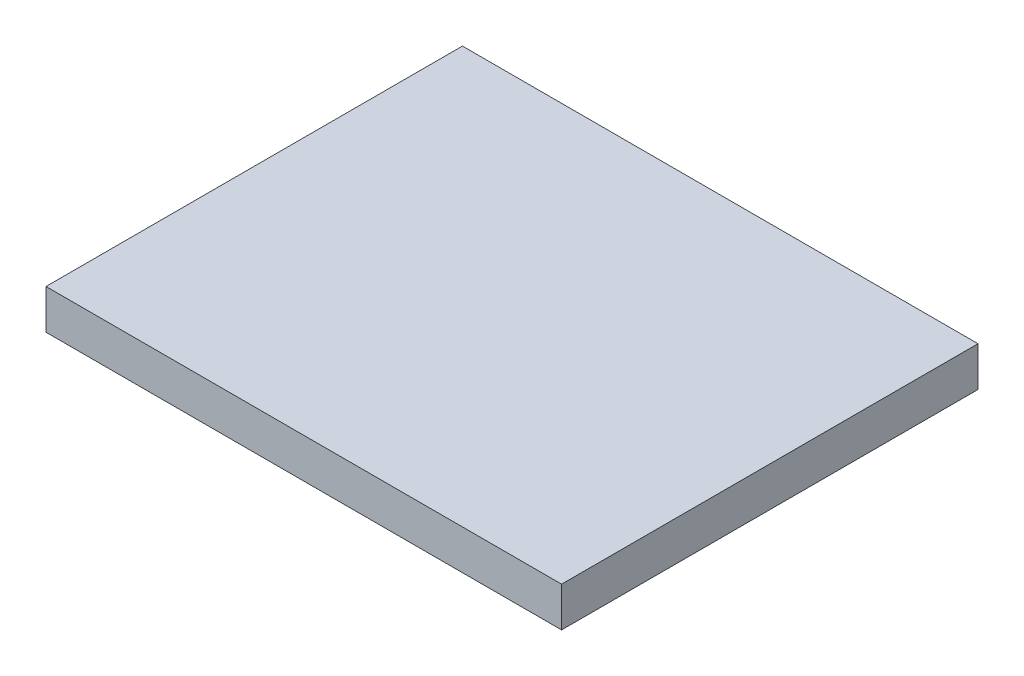
SolidWorks part; units mm, degrees
material "Balsa"
ref_plane "Front Plane" through (0, 0, 0) normal (0, 0, 1) x (1, 0, 0)
ref_plane "Top Plane" through (0, 0, 0) normal (0, 1, 0) x (1, 0, 0)
ref_plane "Right Plane" through (0, 0, 0) normal (1, 0, 0) x (0, 0, -1)
sketch "Sketch2" plane through (0, 0, 0) normal (0, 1, 0) x (1, 0, 0)
  line L1 (650, 525) -> (-650, 525)
  line L2 (650, 525) -> (650, -525)
  line L3 (650, -525) -> (-650, -525)
  line L4 (-650, 525) -> (-650, -525)
  line L5 (650, 525) -> (-650, -525) construction
  line L6 (650, -525) -> (-650, 525) construction
  point P0 (0, 0)
  dimension "D1" = 1300
  dimension "D2" = 1050
extrude "Boss-Extrude1" add sketch "Sketch2" along normal blind 100
